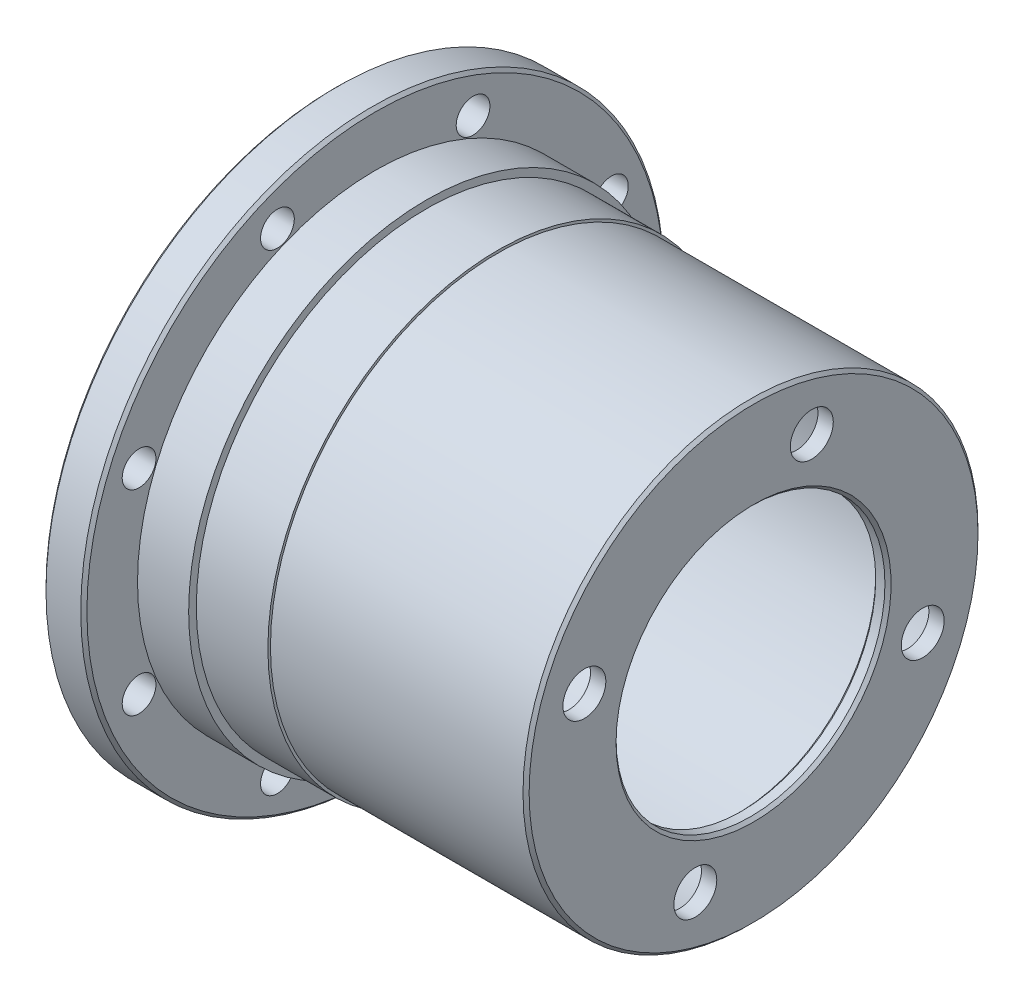
SolidWorks part; units mm, degrees
ref_plane "前视基准面" through (0, 0, 0) normal (0, 0, 1) x (1, 0, 0)
ref_plane "上视基准面" through (0, 0, 0) normal (0, 1, 0) x (1, 0, 0)
ref_plane "右视基准面" through (0, 0, 0) normal (1, 0, 0) x (0, 0, -1)
other "Configuration Table"
sketch "草图1" plane through (0, 0, 0) normal (0, 0, 1) x (1, 0, 0)
  line L0 (0, 0) -> (42970.3286, 0) construction
  line L1 (0, 28.5) -> (0, 21.05)
  line L2 (0, 21.05) -> (39.5, 21.05)
  line L3 (39.5, 21.05) -> (39.5, 13.15)
  line L4 (39.5, 13.15) -> (41, 13.15)
  line L5 (41, 13.15) -> (41, 22.25)
  line L6 (41, 22.25) -> (16, 22.25)
  line L7 (16, 22.25) -> (16, 22.5)
  line L8 (16, 22.5) -> (9, 22.5)
  line L9 (9, 22.5) -> (9, 23.25)
  line L10 (9, 23.25) -> (4, 23.25)
  line L11 (4, 23.25) -> (4, 28.5)
  line L12 (4, 28.5) -> (0, 28.5)
  dimension "D1" = 26.3
  dimension "D2" = 42.1
  dimension "D3" = 44.5
  dimension "D4" = 45
  dimension "D5" = 46.5
  dimension "D6" = 57
  dimension "D7" = 4
  dimension "D8" = 5
  dimension "D9" = 7
  dimension "D10" = 41
  dimension "D11" = 39.5
revolve "旋转1" add sketch "草图1" angle 360 about L0
chamfer "倒角1" distance 0.3 angle 45 5 edges at (39.5, 0, 13.15) (41, 0, 13.15) (4, 0, 28.5) (0, 0, 28.5) (41, 0, 22.25)
sketch "草图7" plane through (41, 0, 0) normal (1, 0, 0) x (0, 0, -1)
  circle A0 centre (0, 17.5) radius 2.1
  dimension "D1" = 4.2
  dimension "D2" = 17.5
extrude "切除-拉伸2" [suppressed] cut sketch "草图7" against normal through all both
sketch "草图2" plane through (41, 0, 0) normal (1, 0, 0) x (0, 0, -1)
  line L0 (5.6974, 16.5466) -> (0, 0) construction
  line L1 (0, 0) -> (50000, 0) construction
  line L2 (0, 0) -> (0, -50000) construction
  circle A0 centre (5.6974, 16.5466) radius 2.1
  dimension "D2" = 4.2
  dimension "D1" = 17.5
  dimension "D3" = 19
extrude "切除-拉伸1" cut sketch "草图2" against normal through all both
pattern_circular "阵列(圆周)1" count 4 over 360 about axis through (0, 0, 0) along (1, 0, 0) of "切除-拉伸1"
hole_wizard "M4 螺纹孔1" positions "草图3" profile "草图4" tap size "M4" standard "GB" end condition through all
sketch "草图3" plane through (0, 0, 0) normal (-1, 0, 0) x (0, 0, 1)
  line L0 (0, 0) -> (50000, 0) construction
  line L1 (0, 0) -> (0, -50000) construction
  line L2 (-9.5671, -23.097) -> (0, 0) construction
  point P0 (-9.5671, -23.097)
  dimension "D1" = 25
  dimension "D2" = 22.5
sketch "草图4" plane through (0, -23.097, -9.5671) normal (0, 1, 0) x (0, 0, 1)
  line L0 (0, 0) -> (0, 41)
  line L1 (0, 41) -> (1.65, 41)
  line L2 (1.65, 41) -> (1.65, 0)
  line L5 (1.65, 0) -> (0, 0)
  line L11 (0, -6.35) -> (0, 107.95) construction
  dimension "通孔螺纹孔钻头直径" = 3.3
  dimension "通孔螺纹孔钻头深度" = 41
cosmetic thread "孔螺蚊线1" parameters "D2"=4
pattern_circular "阵列(圆周)2" count 8 over 360 about axis through (0, 0, 0) along (1, 0, 0) of "M4 螺纹孔1"
sketch "草图6" plane through (0, 0, 0) normal (-1, 0, 0) x (0, 0, 1)
  line L1 (-21.05, -11.2171) -> (21.05, -11.2171)
  line L2 (-21.05, -11.2171) -> (-21.05, 11.2171)
  line L3 (-21.05, 11.2171) -> (21.05, 11.2171)
  line L4 (21.05, -11.2171) -> (21.05, 11.2171)
  line L5 (-21.05, -11.2171) -> (21.05, 11.2171) construction
  line L6 (-21.05, 11.2171) -> (21.05, -11.2171) construction
  circle A0 centre (0, 0) radius 21.05 construction
  circle A1 centre (23.097, 9.5671) radius 1.65 construction
  point P0 (0, 0)
